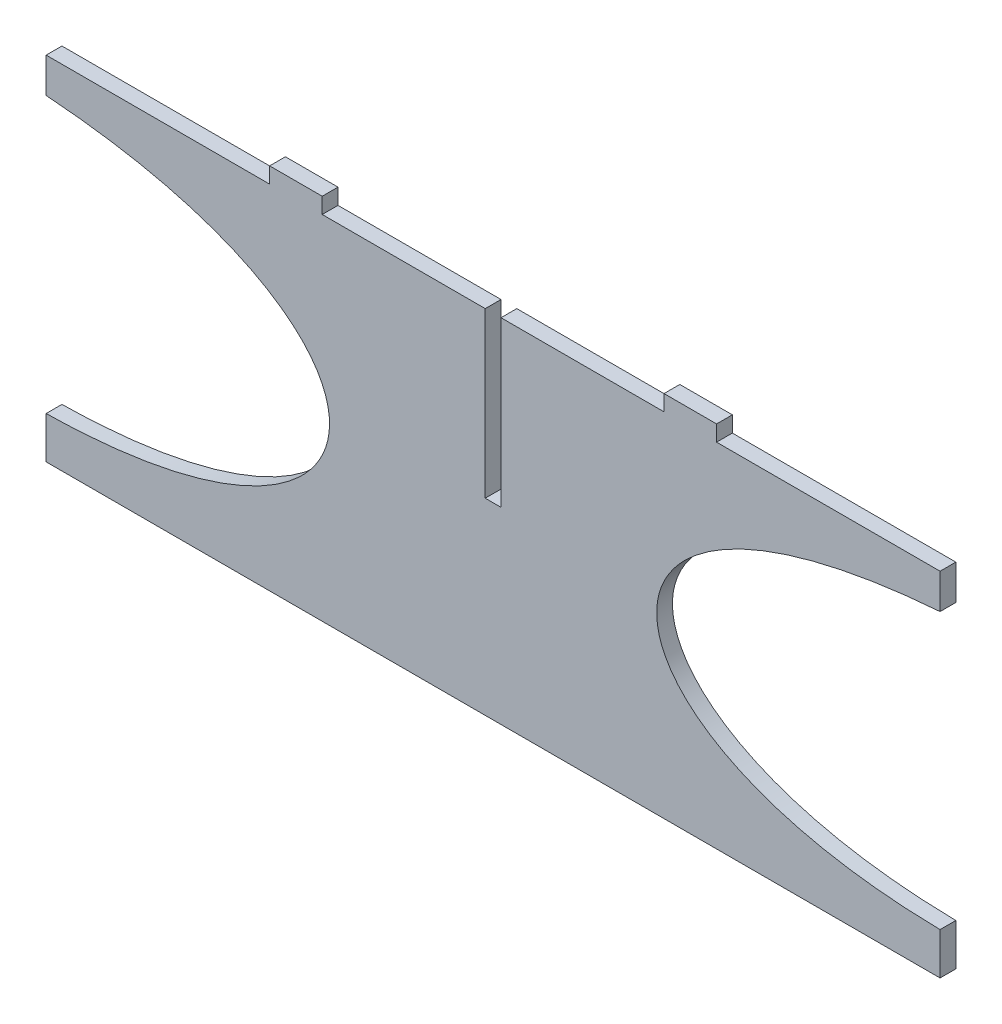
SolidWorks part; units mm, degrees
ref_plane "Plano frontal" through (0, 0, 0) normal (0, 0, 1) x (1, 0, 0)
ref_plane "Plano superior" through (0, 0, 0) normal (0, 1, 0) x (1, 0, 0)
ref_plane "Plano direito" through (0, 0, 0) normal (1, 0, 0) x (0, 0, -1)
sketch "Model" plane through (0, 0, 0) normal (0, 0, 1) x (1, 0, 0)
  line L1 (-58.8502, -40.6768) -> (-58.8502, -45.1121)
  line L2 (-58.8502, -80.0274) -> (-58.8502, -85.3435)
  line L3 (-58.8502, -85.3435) -> (54.4831, -85.3435)
  line L4 (54.4831, -85.3435) -> (54.4831, -80.0274)
  line L5 (54.4831, -45.1121) -> (54.4831, -40.6768)
  line L6 (54.4831, -40.6768) -> (26.1498, -40.6768)
  line L7 (26.1498, -40.6768) -> (26.1498, -38.6717)
  line L8 (26.1498, -38.6717) -> (19.4831, -38.6717)
  line L9 (19.4831, -38.6717) -> (19.4831, -40.6768)
  line L10 (19.4831, -40.6768) -> (-1.1835, -40.6768)
  line L11 (-1.1835, -40.6768) -> (-1.1835, -61.4949)
  line L12 (-1.1835, -61.4949) -> (-3.1835, -61.4949)
  line L13 (-3.1835, -61.4949) -> (-3.1835, -40.6768)
  line L14 (-3.1835, -40.6768) -> (-23.8502, -40.6768)
  line L15 (-23.8502, -40.6768) -> (-23.8502, -38.6717)
  line L16 (-23.8502, -38.6717) -> (-30.5169, -38.6717)
  line L17 (-30.5169, -38.6717) -> (-30.5169, -40.6768)
  line L18 (-30.5169, -40.6768) -> (-58.8502, -40.6768)
  spline S320 degree 3 poles (-58.8502, -45.1121) (-9.0376, -48.8189) (-12.8956, -79.3194) (-58.8502, -80.0274) knots 0.047619 0.047619 0.047619 0.047619 0.095238 0.095238 0.095238 0.095238
  spline S321 degree 3 poles (54.4831, -80.0274) (8.5266, -79.3193) (4.6696, -48.8189) (54.4831, -45.1121) knots 0.238095 0.238095 0.238095 0.238095 0.285714 0.285714 0.285714 0.285714
extrude "Ressalto-extrusão1" add sketch "Model" along normal blind 2
